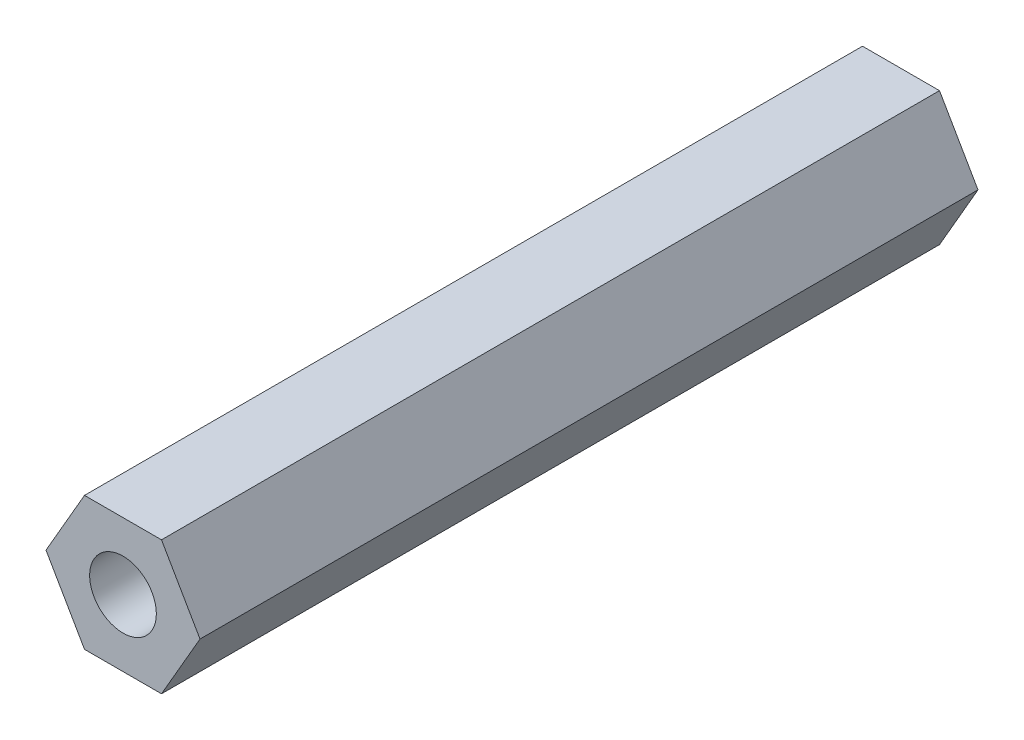
SolidWorks part; units mm, degrees
material "普通碳钢"
ref_plane "前视" through (0, 0, 0) normal (0, 0, 1) x (1, 0, 0)
ref_plane "上视" through (0, 0, 0) normal (0, 1, 0) x (1, 0, 0)
ref_plane "右视" through (0, 0, 0) normal (1, 0, 0) x (0, 0, -1)
sketch "草图1" plane through (0, 0, 0) normal (0, 0, 1) x (1, 0, 0)
  line L0 (0, 0) -> (3.4641, 0)
  line L1 (3.4641, 0) -> (5.1962, -3)
  line L2 (5.1962, -3) -> (3.4641, -6)
  line L3 (3.4641, -6) -> (0, -6)
  line L4 (0, -6) -> (-1.7321, -3)
  line L5 (-1.7321, -3) -> (0, 0)
  dimension "D1" = 6
  dimension "D2" = 6
extrude "凸台-拉伸1" add sketch "草图1" along normal blind 35
sketch "草图2" plane through (0, 0, 35) normal (0, 0, 1) x (1, 0, 0)
  line L0 (1.7321, 0) -> (1.7321, -6) construction
  line L1 (3.4641, 0) -> (0, 0) construction
  line L2 (0, -6) -> (3.4641, -6) construction
  line L3 (5.1962, -3) -> (-1.7321, -3) construction
  circle A0 centre (1.7321, -3) radius 1.5
extrude "切除-拉伸1" cut sketch "草图2" against normal through all
